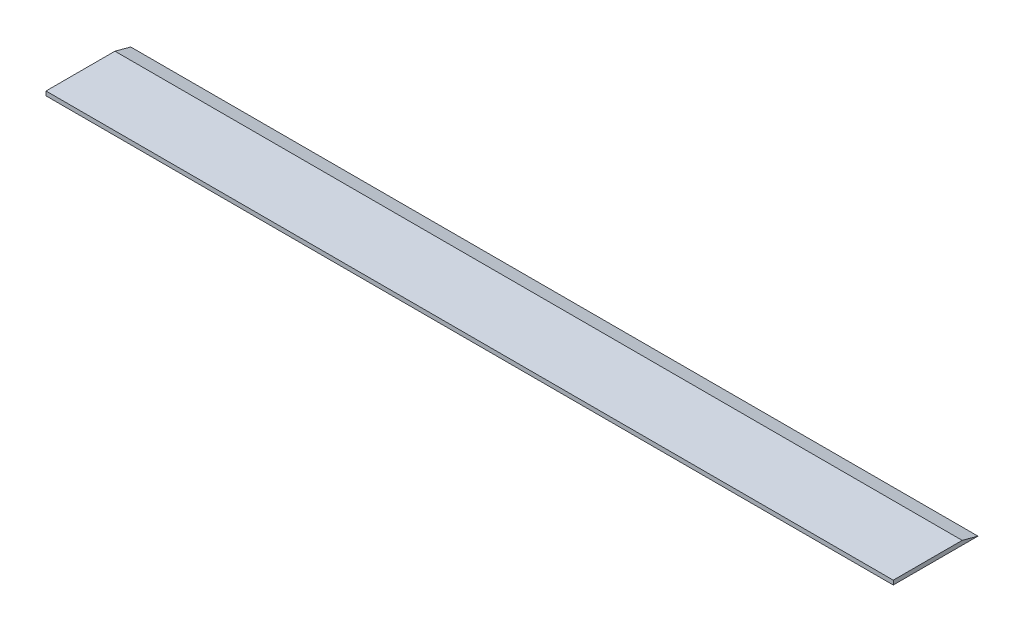
SolidWorks part; units mm, degrees
material "Plain Carbon Steel"
ref_plane "Front Plane" through (0, 0, 0) normal (0, 0, 1) x (1, 0, 0)
ref_plane "Top Plane" through (0, 0, 0) normal (0, 1, 0) x (1, 0, 0)
ref_plane "Right Plane" through (0, 0, 0) normal (1, 0, 0) x (0, 0, -1)
sketch "Sketch1" plane through (0, 0, 0) normal (0, 1, 0) x (1, 0, 0)
  line L1 (-100, -10) -> (100, -10)
  line L2 (-100, -10) -> (-100, 10)
  line L3 (-100, 10) -> (100, 10)
  line L4 (100, -10) -> (100, 10)
  line L5 (-100, -10) -> (100, 10) construction
  line L6 (-100, 10) -> (100, -10) construction
  point P0 (0, 0)
  dimension "D1" = 200
  dimension "D2" = 20
extrude "Blade" add sketch "Sketch1" along normal blind 1
sketch "Sketch2" plane through (100, 0, 0) normal (1, 0, 0) x (0, 0, -1)
  line L0 (6.2679, 1) -> (10, 0)
  line L1 (-10, 1) -> (10, 1) construction
  line L2 (-10, 0) -> (10, 0) construction
  line L3 (10, 0) -> (6.2679, 0)
  line L4 (6.2679, 0) -> (6.2679, 1)
  line L5 (6.2679, 1) -> (10, 1)
  line L6 (10, 1) -> (10, 0)
  line M5 (10, 0) -> (10, 1)
  line M6 (10, 1) -> (-10, 1)
  dimension "D1" = 15
extrude "Cut-Extrude1" cut sketch "Sketch2" against normal through all contours L0 M6 M5
